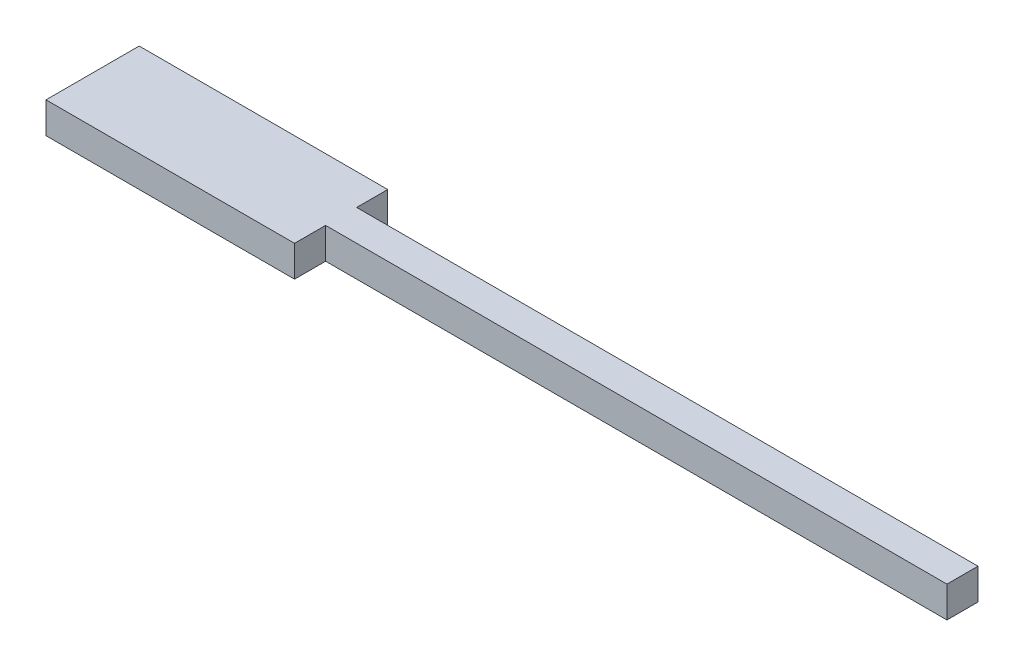
SolidWorks part; units mm, degrees
ref_plane "Front Plane" through (0, 0, 0) normal (0, 0, 1) x (1, 0, 0)
ref_plane "Top Plane" through (0, 0, 0) normal (0, 1, 0) x (1, 0, 0)
ref_plane "Right Plane" through (0, 0, 0) normal (1, 0, 0) x (0, 0, -1)
sketch "Sketch1" plane through (0, 0, 0) normal (0, 1, 0) x (1, 0, 0)
  line L0 (0, 15) -> (0, 10)
  line L1 (0, 0) -> (-40, 0)
  line L3 (0, 15) -> (-40, 15)
  line L4 (-40, 0) -> (-40, 15)
  line L5 (0, 10) -> (100, 10)
  line L7 (0, 5) -> (100, 5)
  line L8 (100, 10) -> (100, 5)
  line L9 (0, 5) -> (0, 0)
extrude "Boss-Extrude1" add sketch "Sketch1" along normal blind 5
